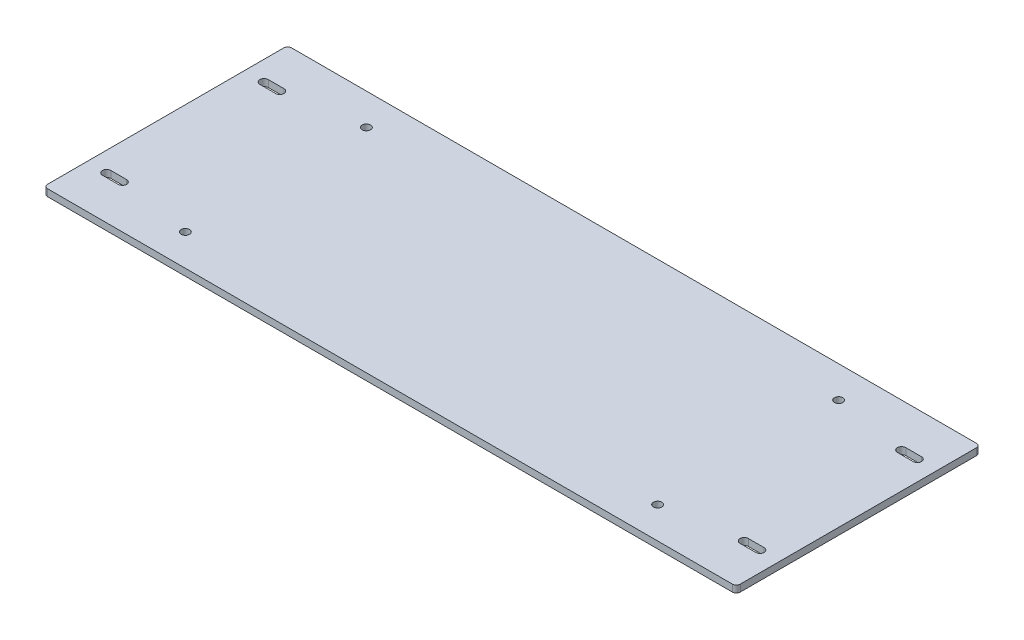
SolidWorks part; units mm, degrees
material "PC High Viscosity"
ref_plane "Front" through (0, 0, 0) normal (0, 0, 1) x (1, 0, 0)
ref_plane "Top" through (0, 0, 0) normal (0, 1, 0) x (1, 0, 0)
ref_plane "Right" through (0, 0, 0) normal (1, 0, 0) x (0, 0, -1)
sketch "Sketch1" plane through (0, 0, 0) normal (0, 1, 0) x (1, 0, 0)
  line L0 (15.875, 34.925) -> (28.575, 34.925) construction
  line L1 (0, 0) -> (558.8, 0)
  line L2 (0, 0) -> (0, 196.85)
  line L3 (0, 196.85) -> (558.8, 196.85)
  line L4 (558.8, 0) -> (558.8, 196.85)
  line L5 (15.875, 38.3032) -> (28.575, 38.3032)
  line L6 (15.875, 31.5468) -> (28.575, 31.5468)
  line L7 (22.225, 34.925) -> (22.225, 161.925) construction
  line L8 (15.875, 161.925) -> (28.575, 161.925) construction
  line L9 (15.875, 165.3032) -> (28.575, 165.3032)
  line L10 (15.875, 158.5468) -> (28.575, 158.5468)
  line L11 (22.225, 161.925) -> (66.675, 161.925) construction
  line L12 (66.675, 161.925) -> (66.675, 34.925) construction
  line L13 (66.675, 34.925) -> (22.225, 34.925) construction
  line L14 (60.325, 161.925) -> (73.025, 161.925) construction
  line L15 (60.325, 165.3032) -> (73.025, 165.3032) construction
  line L16 (60.325, 158.5468) -> (73.025, 158.5468) construction
  line L17 (60.325, 34.925) -> (73.025, 34.925) construction
  line L18 (60.325, 38.3032) -> (73.025, 38.3032) construction
  line L19 (60.325, 31.5468) -> (73.025, 31.5468) construction
  line L20 (536.575, 161.925) -> (536.575, 34.925) construction
  line L21 (542.925, 161.925) -> (530.225, 161.925) construction
  line L22 (542.925, 158.5468) -> (530.225, 158.5468)
  line L23 (542.925, 165.3032) -> (530.225, 165.3032)
  line L24 (542.925, 34.925) -> (530.225, 34.925) construction
  line L25 (542.925, 31.5468) -> (530.225, 31.5468)
  line L26 (542.925, 38.3032) -> (530.225, 38.3032)
  arc A0 (15.875, 38.3032) -> (15.875, 31.5468) centre (15.875, 34.925) ccw
  arc A1 (28.575, 31.5468) -> (28.575, 38.3032) centre (28.575, 34.925) ccw
  arc A2 (15.875, 165.3032) -> (15.875, 158.5468) centre (15.875, 161.925) ccw
  arc A3 (28.575, 158.5468) -> (28.575, 165.3032) centre (28.575, 161.925) ccw
  arc A4 (60.325, 165.3032) -> (60.325, 158.5468) centre (60.325, 161.925) ccw construction
  arc A5 (73.025, 158.5468) -> (73.025, 165.3032) centre (73.025, 161.925) ccw construction
  arc A6 (60.325, 38.3032) -> (60.325, 31.5468) centre (60.325, 34.925) ccw construction
  arc A7 (73.025, 31.5468) -> (73.025, 38.3032) centre (73.025, 34.925) ccw construction
  arc A8 (542.925, 158.5468) -> (542.925, 165.3032) centre (542.925, 161.925) ccw
  arc A9 (530.225, 165.3032) -> (530.225, 158.5468) centre (530.225, 161.925) ccw
  arc A10 (542.925, 31.5468) -> (542.925, 38.3032) centre (542.925, 34.925) ccw
  arc A11 (530.225, 38.3032) -> (530.225, 31.5468) centre (530.225, 34.925) ccw
  point P7 (22.225, 34.925)
  point P13 (22.225, 161.925)
  point P25 (66.675, 161.925)
  point P31 (66.675, 34.925)
  point P40 (536.575, 161.925)
  point P47 (536.575, 34.925)
  dimension "D1" = 6.7564
  dimension "D2" = 34.925
  dimension "D3" = 12.7
  dimension "D4" = 22.225
  dimension "D5" = 127
  dimension "D6" = 34.925
  dimension "D7" = 44.45
  dimension "D8" = 22.225
  dimension "D9" = 514.35
extrude "Boss-Extrude1" add sketch "Sketch1" along normal blind 5.588
fillet "Fillet1" radius 3.175 4 edges at (0, 2.794, -196.85) (558.8, 2.794, -196.85) (0, 2.794, 0) (558.8, 2.794, 0)
sketch "Sketch2" plane through (0, 5.588, 0) normal (0, 1, 0) x (1, 0, 0)
  line L0 (279.4, 196.85) -> (279.4, 0) construction
  line L1 (555.625, 196.85) -> (3.175, 196.85) construction
  line L2 (3.175, 0) -> (555.625, 0) construction
  line L4 (469.9, 25.4) -> (88.9, 25.4) construction
  line L5 (469.9, 25.4) -> (469.9, 171.45) construction
  line L6 (469.9, 171.45) -> (88.9, 171.45) construction
  line L7 (88.9, 25.4) -> (88.9, 171.45) construction
  line L8 (469.9, 25.4) -> (88.9, 171.45) construction
  line L9 (469.9, 171.45) -> (88.9, 25.4) construction
  circle A0 centre (88.9, 171.45) radius 3.3782
  circle A1 centre (88.9, 25.4) radius 3.3782
  circle A2 centre (469.9, 25.4) radius 3.3782
  circle A3 centre (469.9, 171.45) radius 3.3782
  point P6 (279.4, 98.425)
  dimension "D3" = 6.7564
  dimension "D1" = 25.4
  dimension "D2" = 381
extrude "Cut-Extrude1" cut sketch "Sketch2" against normal through all
